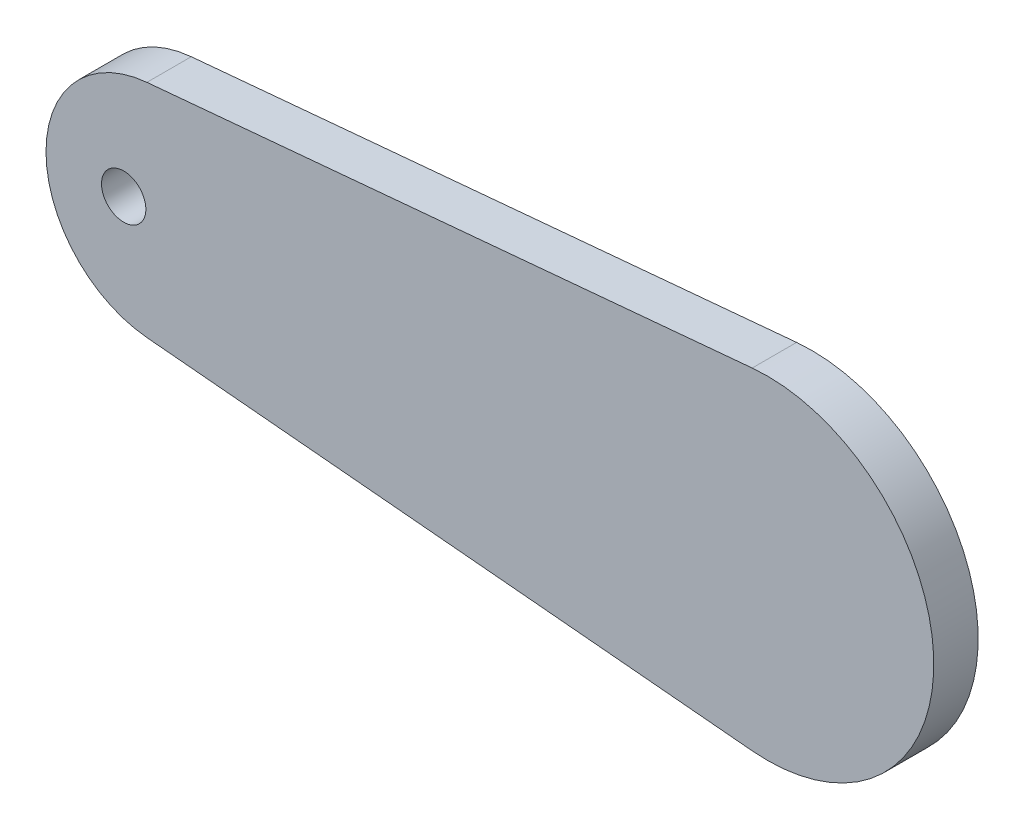
SolidWorks part; units mm, degrees
ref_plane "Front Plane" through (0, 0, 0) normal (0, 0, 1) x (1, 0, 0)
ref_plane "Top Plane" through (0, 0, 0) normal (0, 1, 0) x (1, 0, 0)
ref_plane "Right Plane" through (0, 0, 0) normal (1, 0, 0) x (0, 0, -1)
sketch "Sketch1" plane through (0, 0, 0) normal (0, 0, 1) x (1, 0, 0)
  line L0 (0, 0) -> (55, 0) construction
  line L1 (-0.9091, 9.9586) -> (53.6364, 14.9379)
  line L2 (-0.9091, -9.9586) -> (53.6364, -14.9379)
  arc A0 (-0.9091, 9.9586) -> (-0.9091, -9.9586) centre (0, 0) ccw
  arc A1 (53.6364, 14.9379) -> (53.6364, -14.9379) centre (55, 0) cw
  circle A2 centre (-3, 0) radius 2
  point P9 (-52.831, 32.7729)
  point P10 (-3, 0)
  dimension "D1" = 10
  dimension "D2" = 15
  dimension "D4" = 4
  dimension "D3" = 55
  dimension "D5" = 3
extrude "Boss-Extrude1" add sketch "Sketch1" along normal blind 4
